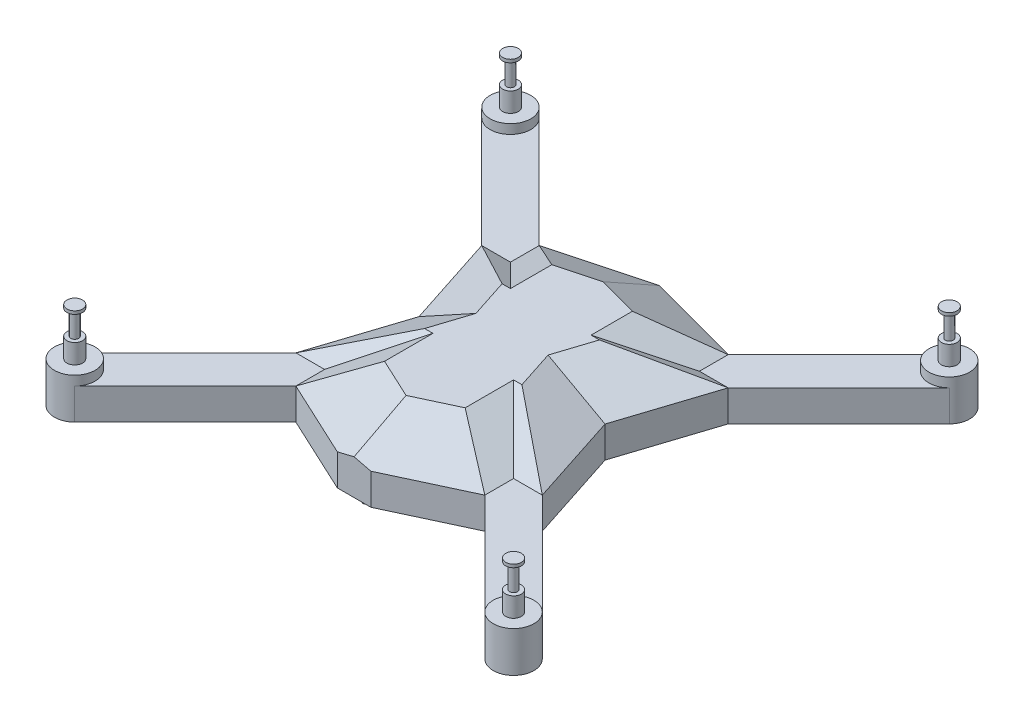
SolidWorks part; units mm, degrees
ref_plane "Alzado" through (0, 0, 0) normal (0, 0, 1) x (1, 0, 0)
ref_plane "Planta" through (0, 0, 0) normal (0, 1, 0) x (1, 0, 0)
ref_plane "Vista lateral" through (0, 0, 0) normal (1, 0, 0) x (0, 0, -1)
sketch "Croquis1" plane through (0, 0, 0) normal (0, 1, 0) x (1, 0, 0)
  line L0 (0, 100) -> (0, -100) construction
  line L1 (30.2115, 91.9049) -> (0, 100)
  line L2 (30.2115, 91.9049) -> (65.5668, 127.2602)
  line L3 (65.5668, 127.2602) -> (74.7592, 118.0678)
  line L4 (74.7592, 118.0678) -> (39.4039, 82.7125)
  line L5 (39.4039, 82.7125) -> (29.7485, 52.9964)
  line L6 (29.7485, 52.9964) -> (39.4039, 23.2802)
  line L7 (39.4039, 23.2802) -> (74.7592, -12.0751)
  line L8 (74.7592, -12.0751) -> (65.5668, -21.2675)
  line L9 (65.5668, -21.2675) -> (30.2115, 14.0878)
  line L10 (30.2115, 14.0878) -> (0, 0)
  line L11 (-65.5668, -21.2675) -> (-30.2115, 14.0878)
  line L12 (-74.7592, -12.0751) -> (-65.5668, -21.2675)
  line L13 (-39.4039, 23.2802) -> (-74.7592, -12.0751)
  line L14 (-29.7485, 52.9964) -> (-39.4039, 23.2802)
  line L15 (-39.4039, 82.7125) -> (-29.7485, 52.9964)
  line L16 (-74.7592, 118.0678) -> (-39.4039, 82.7125)
  line L17 (-65.5668, 127.2602) -> (-74.7592, 118.0678)
  line L18 (-30.2115, 91.9049) -> (-65.5668, 127.2602)
  line L19 (-30.2115, 91.9049) -> (0, 100)
  line L20 (-30.2115, 14.0878) -> (0, 0)
  point P4 (0, 0)
  dimension "D1" = 144
  dimension "D2" = 13
  dimension "D3" = 13
  dimension "D4" = 100
  dimension "D5" = 120
  dimension "D6" = 50
  dimension "D7" = 50
  dimension "D8" = 153
  dimension "D9" = 153
  dimension "D10" = 110
  dimension "D11" = 74.7592
extrude "Saliente-Extruir1" add sketch "Croquis1" along normal blind 10
sketch "Croquis2" plane through (0, 10, 0) normal (0, 1, 0) x (1, 0, 0)
  line L0 (-39.4039, 82.7125) -> (-30.2115, 82.7125)
  line L1 (-30.2115, 82.7125) -> (-30.2115, 91.9049)
  line L2 (-30.2115, 91.9049) -> (0, 100)
  line L3 (0, 100) -> (30.2115, 91.9049)
  line L4 (30.2115, 91.9049) -> (30.2115, 82.7125)
  line L5 (30.2115, 82.7125) -> (39.4039, 82.7125)
  line L6 (39.4039, 82.7125) -> (29.7485, 52.9964)
  line L7 (29.7485, 52.9964) -> (39.4039, 23.2802)
  line L8 (39.4039, 23.2802) -> (30.2115, 23.2802)
  line L9 (30.2115, 23.2802) -> (30.2115, 14.0878)
  line L10 (30.2115, 14.0878) -> (0, 0)
  line L11 (0, 0) -> (-30.2115, 14.0878)
  line L12 (-30.2115, 14.0878) -> (-30.2115, 23.2802)
  line L13 (-30.2115, 23.2802) -> (-39.4039, 23.2802)
  line L14 (-39.4039, 23.2802) -> (-29.7485, 52.9964)
  line L15 (-29.7485, 52.9964) -> (-39.4039, 82.7125)
  dimension "D1" = 90
  dimension "D2" = 90
  dimension "D3" = 90
extrude "Saliente-Extruir2" add sketch "Croquis2" against normal blind 13 draft 20 and the other way blind 10 draft 60
sketch "Croquis3" plane through (0, 10, 0) normal (0, 1, 0) x (1, 0, 0)
  line L0 (65.5668, -21.2675) -> (74.7592, -12.0751) construction
  line L2 (0, 19.1111) -> (0, 0) construction
  line L3 (-11.5367, 52.9964) -> (-29.7485, 52.9964) construction
  circle A0 centre (70.163, -16.6713) radius 6.5
  circle A1 centre (-70.163, -16.6713) radius 6.5
  circle A2 centre (70.163, 122.664) radius 6.5
  circle A3 centre (-70.163, 122.664) radius 6.5
sketch "Croquis8" plane through (0, 0, 0) normal (0, 0, 1) x (1, 0, 0)
  line L1 (-10.8956, -10) -> (10.8956, -10)
  line L2 (-10.8956, -10) -> (-10.8956, 10)
  line L3 (-10.8956, 10) -> (10.8956, 10)
  line L4 (10.8956, -10) -> (10.8956, 10)
  line L5 (-10.8956, -10) -> (10.8956, 10) construction
  line L6 (-10.8956, 10) -> (10.8956, -10) construction
  point P0 (0, 0)
extrude "Cortar-Extruir3" cut sketch "Croquis8" against normal blind 2.5
extrude "Saliente-Extruir3" add sketch "Croquis3" against normal blind 10 and the other way blind 3
sketch "Croquis4" plane through (0, 13, 0) normal (0, 1, 0) x (1, 0, 0)
  line L0 (0, 19.1111) -> (0, 0) construction
  line L1 (-11.5367, 52.9964) -> (-29.7485, 52.9964) construction
  circle A0 centre (70.163, -16.6713) radius 2.5
  circle A1 centre (-70.163, -16.6713) radius 2.5
  circle A2 centre (70.163, 122.664) radius 2.5
  circle A3 centre (-70.163, 122.664) radius 2.5
  dimension "D1" = 5
extrude "Cortar-Extruir1" cut sketch "Croquis4" against normal mid plane 10
sketch "Croquis6" plane through (0, 8, 0) normal (0, 1, 0) x (1, 0, 0)
  circle A0 centre (70.163, -16.6713) radius 2.5 construction
  circle A1 centre (70.163, 122.664) radius 2.5 construction
  circle A2 centre (-70.163, 122.664) radius 2.5 construction
  circle A3 centre (-70.163, -16.6713) radius 2.5 construction
  circle A4 centre (70.163, -16.6713) radius 2.5
  circle A5 centre (70.163, 122.664) radius 2.5
  circle A6 centre (-70.163, 122.664) radius 2.5
  circle A7 centre (-70.163, -16.6713) radius 2.5
extrude "Saliente-Extruir4" add sketch "Croquis6" along normal blind 20 separate body
sketch "Croquis7" plane through (0, 28, 0) normal (0, 1, 0) x (1, 0, 0)
  line L0 (0, 19.1111) -> (0, 0) construction
  line L1 (11.5367, 52.9964) -> (29.7485, 52.9964) construction
  circle A0 centre (-70.163, -16.6713) radius 1.25
  circle A1 centre (70.163, -16.6713) radius 1.25
  circle A2 centre (70.163, 122.664) radius 1.25
  circle A3 centre (-70.163, 122.664) radius 1.25
  circle A4 centre (-70.163, 122.664) radius 2.5 construction
  circle A5 centre (70.163, 122.664) radius 2.5 construction
  circle A6 centre (70.163, -16.6713) radius 2.5 construction
  circle A7 centre (-70.163, -16.6713) radius 2.5 construction
  circle A8 centre (-70.163, 122.664) radius 2.5
  circle A9 centre (70.163, 122.664) radius 2.5
  circle A10 centre (70.163, -16.6713) radius 2.5
  circle A11 centre (-70.163, -16.6713) radius 2.5
  dimension "D1" = 2.5
extrude "Cortar-Extruir2" cut sketch "Croquis7" against normal blind 7.78 from offset 1 offset against normal yes
sketch "Croquis9" plane through (0, 0, -2.5) normal (0, 0, 1) x (1, 0, 0)
  line L0 (5.3613, 10) -> (5.3613, 0) construction
  line L1 (-5.3613, 14.9641) -> (5.3613, 14.9641)
  line L2 (-5.3613, 14.9641) -> (-5.3613, -4.7998)
  line L3 (-5.3613, -4.7998) -> (5.3613, -4.7998)
  line L4 (5.3613, 14.9641) -> (5.3613, -4.7998)
  line L5 (-5.3613, 14.9641) -> (5.3613, -4.7998) construction
  line L6 (-5.3613, -4.7998) -> (5.3613, 14.9641) construction
  line L7 (-5.3613, 0) -> (-5.3613, 10) construction
  point P0 (0, 5.0822)
extrude "Cortar-Extruir5" cut sketch "Croquis9" along normal blind 10
